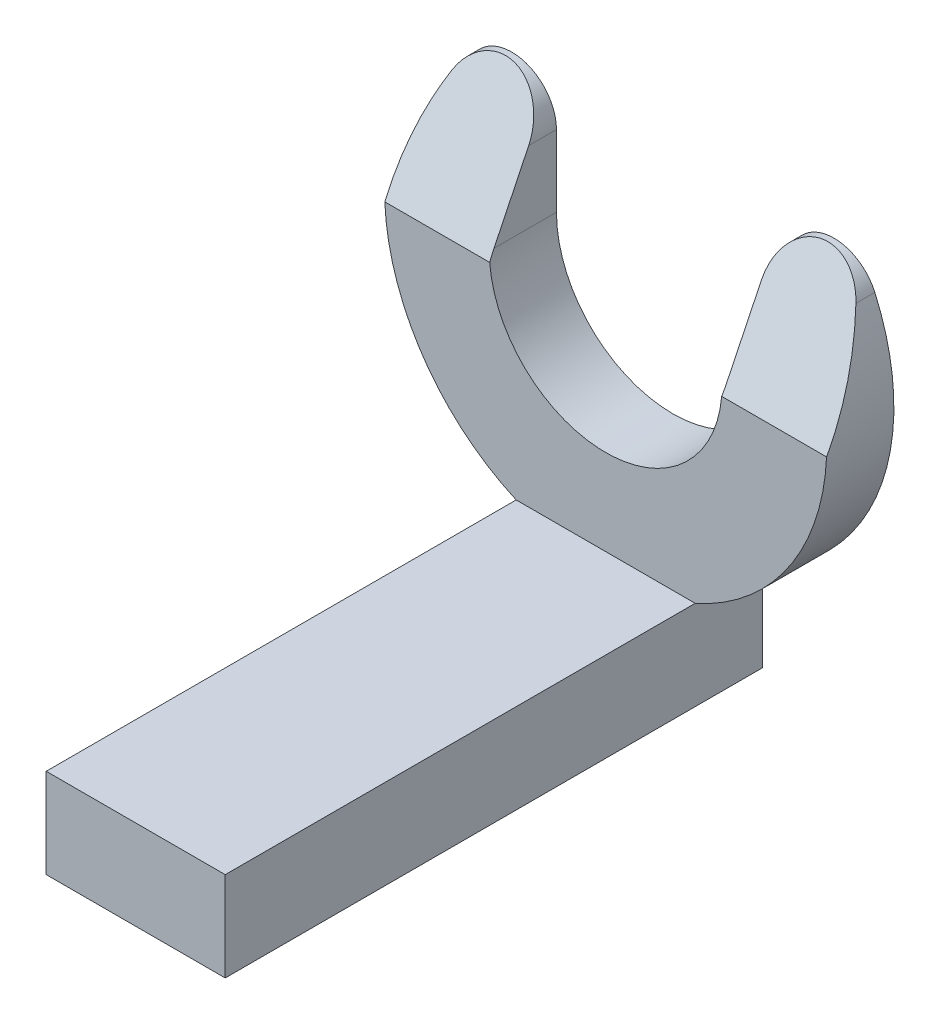
SolidWorks part; units mm, degrees
material "ABS"
ref_plane "Front Plane" through (0, 0, 0) normal (0, 0, 1) x (1, 0, 0)
ref_plane "Top Plane" through (0, 0, 0) normal (0, 1, 0) x (1, 0, 0)
ref_plane "Right Plane" through (0, 0, 0) normal (1, 0, 0) x (0, 0, -1)
sketch "Sketch1" plane through (0, 0, 0) normal (0, 0, 1) x (1, 0, 0)
  line L1 (-2, 0) -> (2, 0)
  line L2 (-2, 0) -> (-2, 2)
  line L3 (-2, 2) -> (2, 2)
  line L4 (2, 0) -> (2, 2)
  dimension "D1" = 4
  dimension "D2" = 2
extrude "Boss-Extrude1" add sketch "Sketch1" along normal blind 12
sketch "Sketch2" plane through (0, 0, 0) normal (0, 0, -1) x (-1, 0, 0)
  line L0 (-2.6, 6.5165) -> (-2.6, 8.1166)
  line L1 (2.6, 6.5165) -> (2.6, 8.1166)
  arc A0 (-4.5138, 8.5227) -> (4.5138, 8.5227) centre (0, 6.5165) ccw
  arc A1 (-2.6, 6.5165) -> (2.6, 6.5165) centre (0, 6.5165) ccw
  arc A2 (-2.6, 8.1166) -> (-4.5138, 8.5227) centre (-3.6, 8.1166) ccw
  arc A3 (4.5138, 8.5227) -> (2.6, 8.1166) centre (3.6, 8.1166) ccw
  dimension "D1" = 9.8791
  dimension "D2" = 5.2
  dimension "D3" = 2
extrude "Boss-Extrude2" add sketch "Sketch2" against normal blind 1.5
sketch "Sketch3" plane through (0, 0, 0) normal (1, 0, 0) x (0, 0, -1)
  line L0 (-0.1353, 9.1166) -> (-1.5, 6.3)
  line L1 (-1.5, 8.5227) -> (-1.5, 2) construction
  line L2 (0, 9.1166) -> (-1.5, 9.1166) construction
  line L3 (0, 8.1166) -> (0, 9.1166) construction
  line L4 (-12, 2) -> (-1.5, 2) construction
  line L5 (-0.1353, 9.1166) -> (-1.5, 9.1166)
  line L6 (-1.5, 9.1166) -> (-1.5, 6.3)
  dimension "D1" = 0.1353
  dimension "D2" = 4.3
extrude "Cut-Extrude2" cut sketch "Sketch3" against normal through all both and the other way through all
